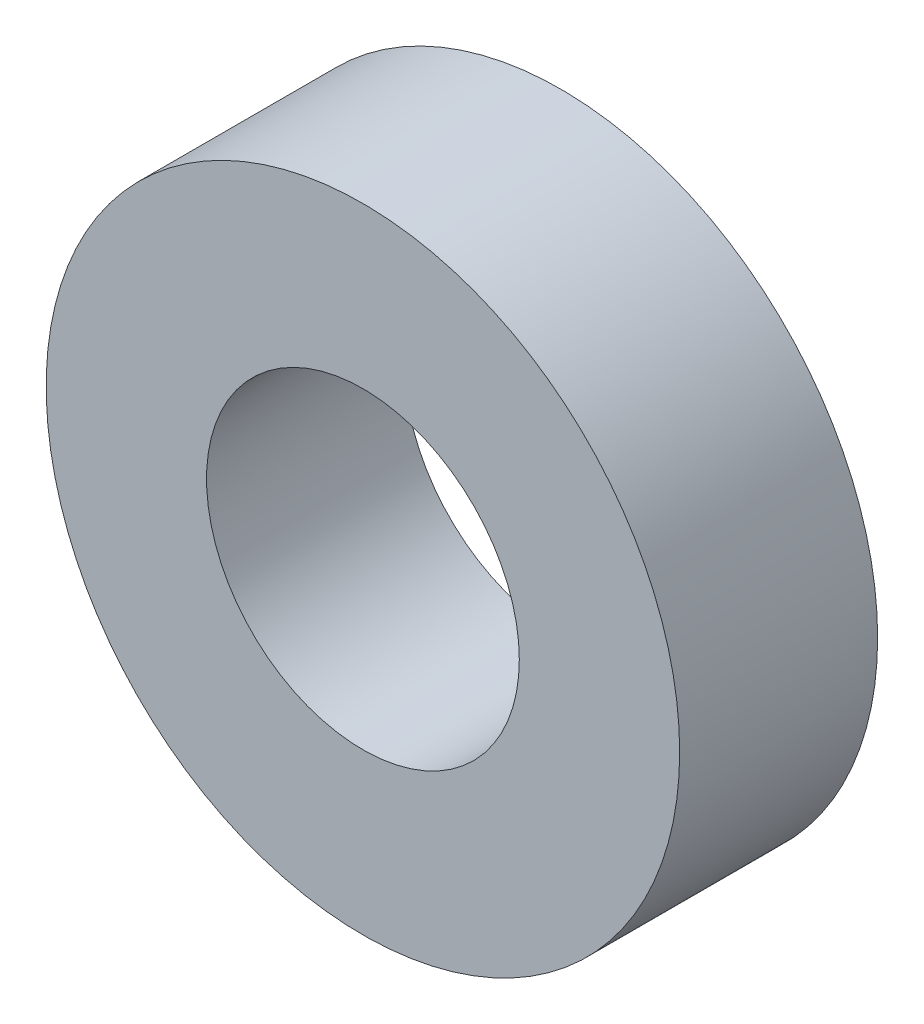
SolidWorks part; units mm, degrees
ref_plane "Front Plane" through (0, 0, 0) normal (0, 0, 1) x (1, 0, 0)
ref_plane "Top Plane" through (0, 0, 0) normal (0, 1, 0) x (1, 0, 0)
ref_plane "Right Plane" through (0, 0, 0) normal (1, 0, 0) x (0, 0, -1)
sketch "Sketch1" plane through (0, 0, 0) normal (0, 0, 1) x (1, 0, 0)
  circle A0 centre (0, 0) radius 3.95
  circle A1 centre (0, 0) radius 8
  dimension "D1" = 7.9
  dimension "D2" = 16
extrude "Boss-Extrude1" add sketch "Sketch1" along normal blind 5
